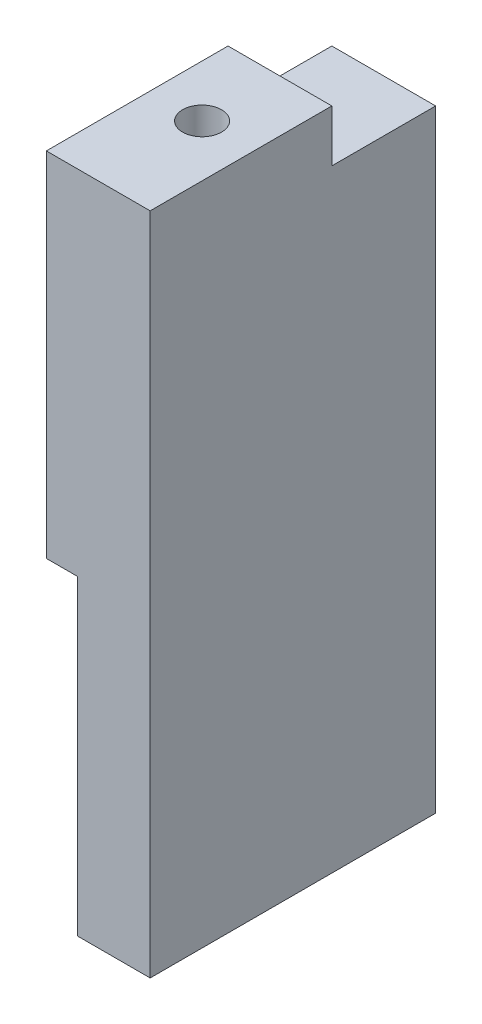
SolidWorks part; units mm, degrees
ref_plane "Front Plane" through (0, 0, 0) normal (0, 0, 1) x (1, 0, 0)
ref_plane "Top Plane" through (0, 0, 0) normal (0, 1, 0) x (1, 0, 0)
ref_plane "Right Plane" through (0, 0, 0) normal (1, 0, 0) x (0, 0, -1)
sketch "Sketch1" plane through (0, 0, 0) normal (0, 1, 0) x (1, 0, 0)
  line L1 (0, 0) -> (25.4, 0)
  line L2 (0, 0) -> (0, 69.85)
  line L3 (0, 69.85) -> (25.4, 69.85)
  line L4 (25.4, 0) -> (25.4, 69.85)
  dimension "D1" = 25.4
  dimension "D2" = 69.85
extrude "Boss-Extrude1" add sketch "Sketch1" along normal blind 162.56
sketch "Sketch2" plane through (0, 162.56, 0) normal (0, 1, 0) x (1, 0, 0)
  line L0 (0, 0) -> (25.4, 0) construction
  line L1 (0, 69.85) -> (0, 0) construction
  circle A0 centre (12.7, 25.4) radius 4.7625
  dimension "D1" = 9.525
  dimension "D2" = 25.4
  dimension "D3" = 12.7
extrude "Cut-Extrude1" cut sketch "Sketch2" against normal blind 50.8
sketch "Sketch3" plane through (0, 0, 0) normal (0, 0, 1) x (1, 0, 0)
  line L1 (0, 0) -> (7.62, 0)
  line L2 (0, 0) -> (0, 76.2)
  line L3 (0, 76.2) -> (7.62, 76.2)
  line L4 (7.62, 0) -> (7.62, 76.2)
  dimension "D1" = 7.62
  dimension "D2" = 76.2
extrude "Cut-Extrude2" cut sketch "Sketch3" against normal through all
sketch "Sketch4" plane through (25.4, 0, 0) normal (1, 0, 0) x (0, 0, -1)
  line L1 (69.85, 162.56) -> (44.45, 162.56)
  line L2 (69.85, 162.56) -> (69.85, 149.86)
  line L3 (69.85, 149.86) -> (44.45, 149.86)
  line L4 (44.45, 162.56) -> (44.45, 149.86)
  point P5 (44.45, 156.21)
  point P6 (69.85, 156.21)
  dimension "D1" = 12.7
  dimension "D2" = 25.4
extrude "Cut-Extrude3" cut sketch "Sketch4" against normal through all
sketch "Sketch5" plane through (0, 0, -69.85) normal (0, 0, -1) x (-1, 0, 0)
  line L0 (13.97, 0) -> (-13.97, 0) construction
  line L1 (-25.4, 149.86) -> (-25.4, 0) construction
  circle A0 centre (-17.78, 12.7) radius 1.1616
  circle A1 centre (-17.78, 43.18) radius 1.0827
  dimension "D1" = 12.7
  dimension "D2" = 7.62
  dimension "D3" = 30.48
hole_wizard "1/4-20 Tapped Hole1" positions "Sketch6" profile "Sketch7" tap size "1/4-20" standard "ANSI Inch"
sketch "Sketch6" plane through (0, 0, -69.85) normal (0, 0, -1) x (-1, 0, 0)
  point P0 (-17.78, 43.18)
  point P3 (-17.78, 12.7)
sketch "Sketch7" plane through (17.78, 43.18, -69.85) normal (1, 0, 0) x (0, 1, 0)
  line L0 (0, 0) -> (0, 24.3938)
  line L1 (0, 24.3938) -> (2.5527, 22.86)
  line L2 (2.5527, 22.86) -> (2.5527, 0)
  line L5 (2.5527, 0) -> (0, 0)
  line L10 (0, 24.3938) -> (-2.5527, 22.86) construction
  line L11 (0, -6.35) -> (0, 107.95) construction
  dimension "Tap Drill Dia." = 5.1054
  dimension "Tap Drill Depth" = 22.86
  dimension "Drill Angle" = 118
cosmetic thread "Hole Thread1" parameters "D1"=19.05, "D2"=6.35
cosmetic thread "Hole Thread2" parameters "D1"=19.05, "D2"=6.35
move or copy body "Body-Move/Copy1" [suppressed] bodies to move or copy 105
